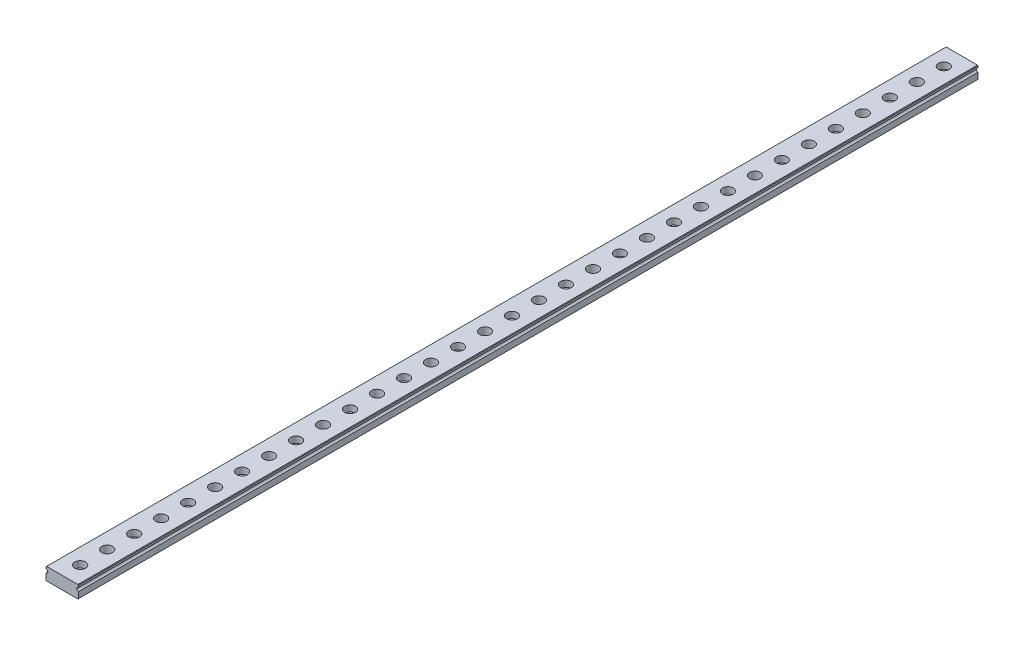
SolidWorks part; units mm, degrees
material "AISI 1020"
ref_plane "Front Plane" through (0, 0, 0) normal (0, 0, 1) x (1, 0, 0)
ref_plane "Top Plane" through (0, 0, 0) normal (0, 1, 0) x (1, 0, 0)
ref_plane "Right Plane" through (0, 0, 0) normal (1, 0, 0) x (0, 0, -1)
ref_plane "Plano1" through (0, 0, 0) normal (0, -1, 0) x (1, 0, 0)
sketch "Esboço1" plane through (0, 0, 0) normal (0, -1, 0) x (1, 0, 0)
  line L0 (-18, -500) -> (0, -500)
  line L1 (0, -500) -> (0, 0)
  line L2 (0, 0) -> (-18, 0)
  line L3 (-18, 0) -> (-18, -500)
  dimension "D1" = 500
  dimension "D2" = 18
extrude "Ressalto-extrusão1" add sketch "Esboço1" against normal blind 7
hole_wizard "Furo de diâmetro Ø2.0 (2)1" positions "Esboço5" profile "Esboço4" hole size "Ø2.0" standard "Ansi Metric" end condition through all
sketch "Esboço5" plane through (0, 0, -500) normal (0, 0, -1) x (-1, 0, 0)
  line L0 (0, 0) -> (18, 0) construction
  line L1 (18, 7) -> (18, 0) construction
  point P0 (0, 4.7)
  point P1 (18, 4.7)
  dimension "D1" = 18
  dimension "D2" = 4.7
sketch "Esboço4" plane through (0, 4.7, -500) normal (1, 0, 0) x (0, 1, 0)
  line L0 (0, 0) -> (0, 500)
  line L1 (0, 500) -> (1, 500)
  line L2 (1, 500) -> (1, 0)
  line L5 (1, 0) -> (0, 0)
  line L11 (0, -6.35) -> (0, 107.95) construction
  dimension "Thru Hole Dia." = 2
  dimension "Thru Hole Depth" = 500
hole_wizard "Furo de diâmetro Ø6.0 (6)1" positions "Esboço3" profile "Esboço2" hole size "Ø6.0" standard "Ansi Metric" end condition through all
sketch "Esboço3" plane through (0, 7, 0) normal (0, 1, 0) x (1, 0, 0)
  line L0 (0, 500) -> (0, 0) construction
  line L1 (0, 0) -> (-18, 0) construction
  point P0 (-9, 25)
  dimension "D3" = 9
  dimension "D4" = 25
sketch "Esboço2" plane through (-9, 7, -25) normal (1, 0, 0) x (0, 0, 1)
  line L0 (0, 0) -> (0, 7)
  line L1 (0, 7) -> (3, 7)
  line L2 (3, 7) -> (3, 0)
  line L5 (3, 0) -> (0, 0)
  line L11 (0, -6.35) -> (0, 107.95) construction
  dimension "Thru Hole Dia." = 6
  dimension "Thru Hole Depth" = 7
hole_wizard "Rebaixo para parafuso de máquina de cabeça sextavada de M31" positions "Esboço9" profile "Esboço8" counterbore size "M3" standard "Ansi Metric" end condition through all
sketch "Esboço9" plane through (0, 7, 0) normal (0, 1, 0) x (1, 0, 0)
  line L0 (0, 500) -> (0, 0) construction
  line L3 (0, 0) -> (-18, 0) construction
  point P2 (-9, 10)
  dimension "D3" = 9
  dimension "D6" = 10
sketch "Esboço8" plane through (-9, 7, -10) normal (1, 0, 0) x (0, 0, 1)
  line L0 (0, 0) -> (0, 7)
  line L1 (0, 7) -> (1.75, 7)
  line L3 (1.75, 7) -> (1.75, 3.5)
  line L4 (1.75, 3.5) -> (3, 3.5)
  line L5 (3, 3.5) -> (3, 0)
  line L7 (3, 0) -> (0, 0)
  line L11 (0, -6.35) -> (0, 107.95) construction
  dimension "Thru Hole Dia." = 3.5
  dimension "Thru Hole Depth" = 7
  dimension "C'Bore Dia." = 6
  dimension "C'Bore Depth" = 3.5
pattern_linear "Padrão linear1" count 16 spacing 30 along (0, 0, -1) of "Furo de diâmetro Ø6.0 (6)1"
pattern_linear "Padrão linear2" count 17 spacing 30 along (0, 0, -1) of "Rebaixo para parafuso de máquina de cabeça sextavada de M31"
chamfer "Chanfro1" distance 0.3 angle 45 4 edges at (-18, 7, -250) (0, 7, -250) (0, 0, -250) (-18, 0, -250)
